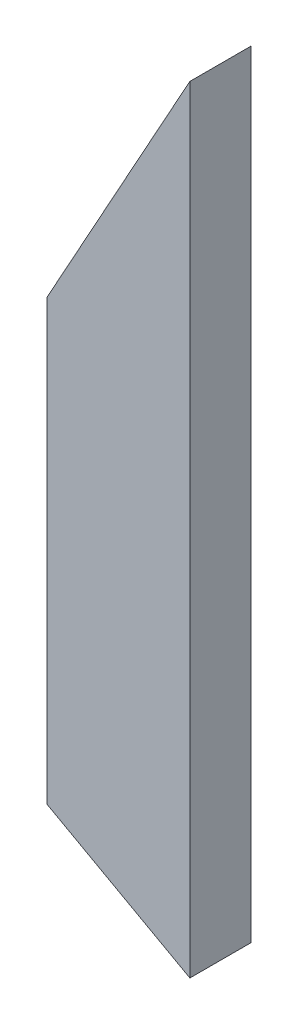
SolidWorks part; units mm, degrees
material "Balsa"
ref_plane "Front Plane" through (0, 0, 0) normal (0, 0, 1) x (1, 0, 0)
ref_plane "Top Plane" through (0, 0, 0) normal (0, 1, 0) x (1, 0, 0)
ref_plane "Right Plane" through (0, 0, 0) normal (1, 0, 0) x (0, 0, -1)
sketch "Sketch1" plane through (0, 0, 0) normal (0, 0, 1) x (1, 0, 0)
  line L0 (44.45, 241.3) -> (-44.45, 80.5378)
  line L1 (-44.45, 241.3) -> (44.45, 241.3)
  line L2 (-44.45, 241.3) -> (-44.45, -241.3)
  line L3 (-44.45, -241.3) -> (44.45, -241.3)
  line L4 (44.45, 241.3) -> (44.45, -241.3)
  line L5 (-44.45, 241.3) -> (44.45, -241.3) construction
  line L6 (-44.45, -241.3) -> (44.45, 241.3) construction
  line L7 (44.45, -241.3) -> (-44.45, -192.1131)
  point P0 (0, 0)
  dimension "D1" = 482.6
  dimension "D2" = 88.9
  dimension "D3" = 183.7055
  dimension "D4" = 101.6
extrude "Boss-Extrude1" add sketch "Sketch1" along normal blind 38.1
